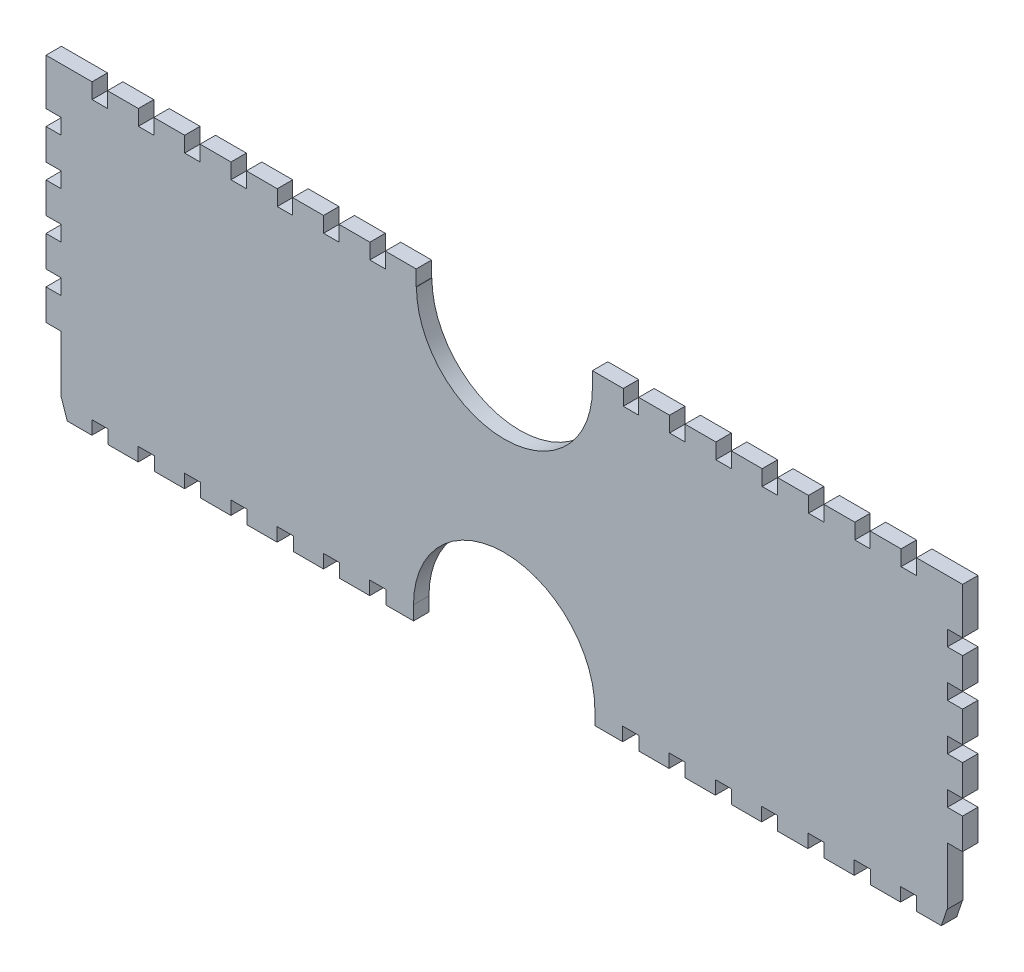
SolidWorks part; units mm, degrees
ref_plane "Plan de face" through (0, 0, 0) normal (0, 0, 1) x (1, 0, 0)
ref_plane "Plan de dessus" through (0, 0, 0) normal (0, 1, 0) x (1, 0, 0)
ref_plane "Plan de droite" through (0, 0, 0) normal (1, 0, 0) x (0, 0, -1)
sketch "Esquisse1" plane through (0, 0, 0) normal (0, 0, 1) x (1, 0, 0)
  line L1 (252.5377, 15.0898) -> (-44.3756, 15.0898)
  line L2 (252.5377, 15.0898) -> (252.5377, -84.1129)
  line L3 (252.5377, -84.1129) -> (-44.3756, -84.1129)
  line L4 (-44.3756, 15.0898) -> (-44.3756, -84.1129)
extrude "Boss.-Extru.1" add sketch "Esquisse1" along normal blind 5
sketch "Esquisse2" plane through (0, 0, 0) normal (0, 0, -1) x (-1, 0, 0)
  line L0 (44.3756, -78.5106) -> (39.3756, -78.5106)
  line L3 (39.3756, -78.5106) -> (37.5047, -84.1129)
  line L4 (44.3756, -84.1129) -> (-252.5377, -84.1129) construction
  line L5 (37.5047, -84.1129) -> (44.3756, -84.1129)
  line L6 (44.3756, -84.1129) -> (44.3756, -78.5106)
extrude "Enlèv. mat.-Extru.1" cut sketch "Esquisse2" against normal blind 10
sketch "Esquisse3" plane through (0, 0, 0) normal (0, 0, -1) x (-1, 0, 0)
  line L0 (37.5047, -84.1129) -> (-252.5377, -84.1129) construction
  line L1 (29.5047, -84.1129) -> (24.2754, -84.1129)
  line L2 (29.5047, -84.1129) -> (29.5047, -79.7167)
  line L3 (29.5047, -79.7167) -> (24.2754, -79.7167)
  line L4 (24.2754, -84.1129) -> (24.2754, -79.7167)
extrude "Enlèv. mat.-Extru.2" cut sketch "Esquisse3" against normal blind 10
pattern_linear "Répétition linéaire1" count 7 spacing 15 along (1, 0, 0) of "Enlèv. mat.-Extru.2"
ref_plane "Plan1" through (104.0811, 0, 0) normal (-1, 0, 0) x (0, 0, 1)
mirror "Symétrie1" about plane through (104.0811, 0, 0) normal (-1, 0, 0) of "Répétition linéaire1", "Enlèv. mat.-Extru.1", "Enlèv. mat.-Extru.2"
sketch "Esquisse4" plane through (0, 0, 0) normal (0, 0, -1) x (-1, 0, 0)
  line L0 (-65.7246, -84.1129) -> (-142.4375, -84.1129) construction
  line L1 (-74.6821, -84.1129) -> (-133.4204, -84.1129)
  line L2 (-74.6821, -84.1129) -> (-74.6821, -79.5725)
  line L3 (-74.6821, -79.5725) -> (-133.4204, -79.5725)
  line L4 (-133.4204, -84.1129) -> (-133.4204, -79.5725)
extrude "Enlèv. mat.-Extru.3" cut sketch "Esquisse4" against normal blind 10
sketch "Esquisse5" plane through (0, 0, 0) normal (0, 0, -1) x (-1, 0, 0)
  line L0 (-74.6821, -79.5725) -> (-133.4204, -79.5725) construction
  line L1 (-74.6821, -79.5725) -> (-133.4204, -79.5725)
  arc A0 (-133.4204, -79.5725) -> (-74.6821, -79.5725) centre (-104.0512, -79.5725) cw
extrude "Enlèv. mat.-Extru.4" cut sketch "Esquisse5" against normal blind 10
sketch "Esquisse6" plane through (0, 0, 5) normal (0, 0, 1) x (1, 0, 0)
  line L0 (252.5377, 15.0898) -> (-44.3756, 15.0898) construction
  line L1 (237.6244, 10.0898) -> (232.6244, 10.0898)
  line L2 (237.6244, 10.0898) -> (237.6244, 15.0898)
  line L3 (237.6244, 15.0898) -> (232.6244, 15.0898)
  line L4 (232.6244, 10.0898) -> (232.6244, 15.0898)
  dimension "D1" = 5
extrude "Enlèv. mat.-Extru.5" cut sketch "Esquisse6" against normal blind 5
pattern_linear "Répétition linéaire2" count 8 spacing 15 along (-1, 0, 0) of "Enlèv. mat.-Extru.5"
sketch "Esquisse7" plane through (0, 0, 5) normal (0, 0, 1) x (1, 0, 0)
  line L1 (132.6244, 15.0898) -> (75.6244, 15.0898)
  line L2 (132.6244, 15.0898) -> (132.6244, 10.0898)
  line L3 (132.6244, 10.0898) -> (75.6244, 10.0898)
  line L4 (75.6244, 15.0898) -> (75.6244, 10.0898)
extrude "Enlèv. mat.-Extru.6" cut sketch "Esquisse7" against normal blind 5
sketch "Esquisse8" plane through (0, 0, 5) normal (0, 0, 1) x (1, 0, 0)
  line L0 (132.6244, 10.0898) -> (75.6244, 10.0898) construction
  line L1 (132.6244, 15.0898) -> (132.6244, 10.0898) construction
  line L2 (75.6244, 10.0898) -> (132.6244, 10.0898) construction
  line L3 (75.6244, 10.0898) -> (132.6244, 10.0898)
  arc A0 (132.6244, 10.0898) -> (75.6244, 10.0898) centre (104.1244, 10.0898) cw
extrude "Enlèv. mat.-Extru.7" cut sketch "Esquisse8" against normal blind 5 contours A0 L3
ref_plane "Plan2" through (104.0811, 0, 0) normal (1, 0, 0) x (0, 0, -1)
mirror "Symétrie2" about plane through (104.0811, 0, 0) normal (1, 0, 0) of "Répétition linéaire2", "Enlèv. mat.-Extru.5"
sketch "Esquisse9" plane through (0, 0, 5) normal (0, 0, 1) x (1, 0, 0)
  line L1 (247.6244, -59.9102) -> (252.5377, -59.9102)
  line L2 (247.6244, -59.9102) -> (247.6244, -78.5106)
  line L3 (247.6244, -78.5106) -> (252.5377, -78.5106)
  line L4 (252.5377, -59.9102) -> (252.5377, -78.5106)
extrude "Enlèv. mat.-Extru.8" cut sketch "Esquisse9" against normal blind 5
sketch "Esquisse10" plane through (0, 0, 5) normal (0, 0, 1) x (1, 0, 0)
  line L0 (252.6244, -44.9102) -> (252.6244, -49.9102) construction
  line L1 (247.6244, -49.9102) -> (252.6244, -49.9102)
  line L2 (247.6244, -49.9102) -> (247.6244, -44.9102)
  line L3 (247.6244, -44.9102) -> (252.6244, -44.9102)
  line L4 (252.6244, -49.9102) -> (252.6244, -44.9102)
  line L5 (247.6244, -44.9102) -> (252.6244, -44.9102) construction
extrude "Enlèv. mat.-Extru.9" cut sketch "Esquisse10" against normal blind 5
pattern_linear "Répétition linéaire3" count 4 spacing 15 along (0, 1, 0) of "Enlèv. mat.-Extru.9"
ref_plane "Plan3" through (104.0811, 0, 0) normal (1, 0, 0) x (0, 0, -1)
mirror "Symétrie3" about plane through (104.0811, 0, 0) normal (1, 0, 0) of "Enlèv. mat.-Extru.8", "Répétition linéaire3", "Enlèv. mat.-Extru.9"
